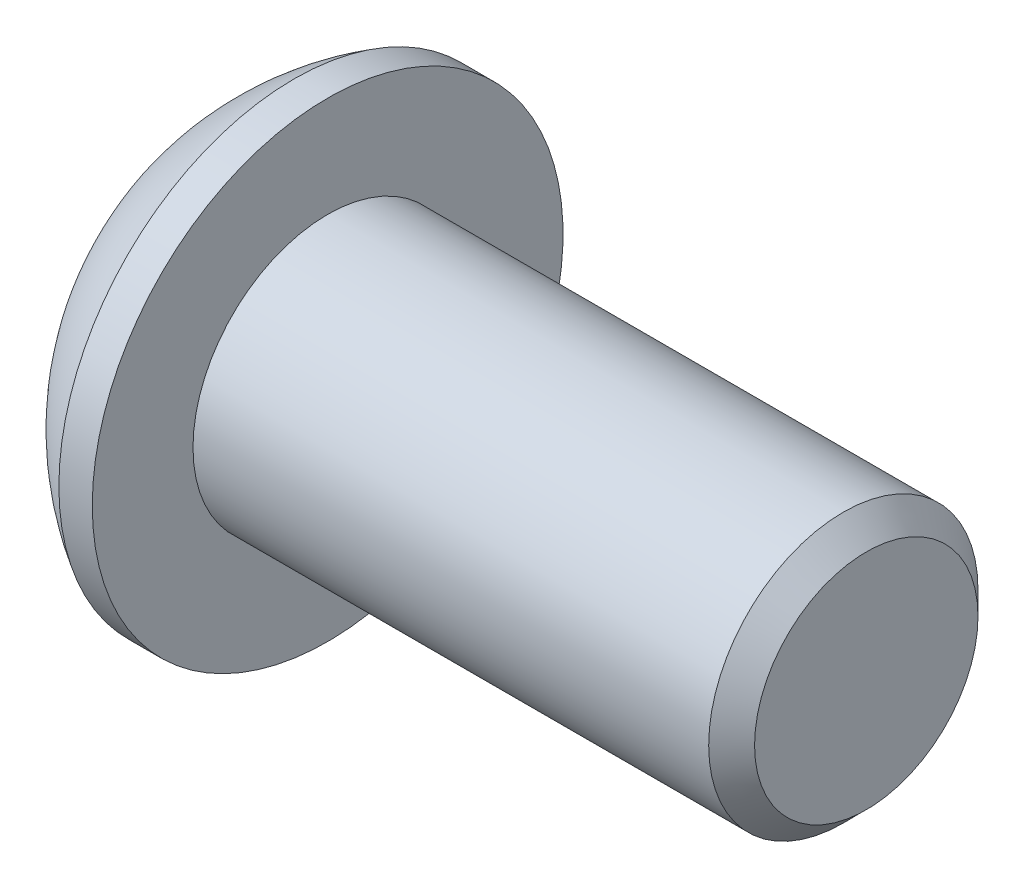
SolidWorks part; units mm, degrees
ref_plane "Plane1" through (0, 0, 0) normal (0, 0, 1) x (1, 0, 0)
ref_plane "Plane2" through (0, 0, 0) normal (0, 1, 0) x (1, 0, 0)
ref_plane "Plane3" through (0, 0, 0) normal (1, 0, 0) x (0, 0, -1)
sketch "BodySke" plane through (0, 0, 0) normal (0, 0, 1) x (1, 0, 0)
  line L0 (16.0528, 0) -> (16.0528, 2.634)
  line L1 (15.5118, 3.175) -> (3.3528, 3.175)
  line L2 (3.3528, 3.175) -> (3.3528, 5.5499)
  line L3 (3.3528, 5.5499) -> (2.5654, 5.5499)
  line L4 (0, 0) -> (101.6, 0) construction
  line L5 (3.3528, -5.5499) -> (2.5654, -5.5499) construction
  line L6 (55.6768, -3.175) -> (3.3528, -3.175) construction
  line L7 (16.0528, 0) -> (0, 0)
  line L8 (0, 2.775) -> (0, -2.775) construction
  line L9 (0, 0) -> (0, 2.775)
  line L10 (16.0528, 2.634) -> (15.5118, 3.175)
  line L11 (16.0528, -2.634) -> (15.5118, -3.175) construction
  line L12 (4.2596, 9.525) -> (4.2596, -3.175) construction
  line L13 (3.3528, 9.525) -> (3.3528, -3.175) construction
  arc A1 (0, 2.775) -> (2.5654, 5.5499) centre (5.7851, 0) cw
  dimension "Diameter" = 6.35
  dimension "Length" = 12.7
  dimension "Head_dia" = 11.0998
  dimension "D1" = 5.5499
  dimension "Head_ht" = 3.3528
  dimension "Head_side_ht" = 0.7874
  dimension "Minor_dia" = 5.268
  dimension "Body_ch_ang" = 45
  dimension "Advance" = 0.9068
  dimension "Thread_nom" = 12.7
revolve "BaseBody" add sketch "BodySke" angle 360 about L4
cosmetic thread "ThreadCosmetic" [suppressed] parameters "Thread_length"=11.7932, "Thread_minor"=5.268
sketch "Sketch2" plane through (0, 0, 0) normal (0, 0, 1) x (1, 0, 0)
  line L0 (0, 1.9812) -> (2.2098, 1.9812)
  line L1 (2.2098, 1.9812) -> (3.3536, 0)
  line L3 (3.3536, 0) -> (0, 0)
  line L4 (0, 0) -> (0, 1.9812)
  line L5 (0, -1.9812) -> (2.2098, -1.9812) construction
  line L6 (0, 0) -> (47.625, 0) construction
  dimension "D2" = 60
  dimension "PreBroach_depth" = 2.2098
  dimension "PreBroach_dia" = 3.9624
revolve "PreBroach" cut sketch "Sketch2" angle 360 about L6
sketch "Sketch3" plane through (0, 0, 0) normal (1, 0, 0) x (0, 0, -1)
  line L0 (-1.9812, -1.1438) -> (-1.9812, 1.1438)
  line L1 (-1.9812, 1.1438) -> (0, 2.2877)
  line L2 (0, 2.2877) -> (1.9812, 1.1438)
  line L3 (1.9812, 1.1438) -> (1.9812, -1.1438)
  line L4 (1.9812, -1.1438) -> (0, -2.2877)
  line L5 (0, -2.2877) -> (-1.9812, -1.1438)
  dimension "Hex_size" = 3.9624
  dimension "D3" = 3.9624
  dimension "D1" = 1.9812
  dimension "D2" = 1.9812
extrude "Hex" cut sketch "Sketch3" along normal blind 2.2098
sketch "Sketch4" plane through (0, 9.525, 0) normal (1, 0, 0) x (0, 0, -1)
  line L0 (0, -9.525) -> (2.3876, -9.525)
  line L1 (0, -9.525) -> (6.1484, -5.9752) construction
  line L2 (0, -9.525) -> (1.1938, -7.4573)
  line L3 (1.9883, -8.949) -> (2.2704, -8.7861)
  line L4 (1.493, -8.0911) -> (1.7751, -7.9282)
  arc A0 (1.9883, -8.949) -> (1.493, -8.0911) centre (0, -9.525) ccw
  arc A1 (2.3876, -9.525) -> (2.2704, -8.7861) centre (0, -9.525) ccw
  arc A2 (1.1938, -7.4573) -> (1.7751, -7.9282) centre (0, -9.525) cw
  dimension "Spline_n_dim" = 4.1402
  dimension "Spline_m_dim" = 4.7752
  dimension "D1" = 30
  dimension "D2" = 60
  dimension "Spline_p_dim" = 0.9906
  dimension "D3" = 0.4953
extrude "Spline" [suppressed] cut sketch "Sketch4" along normal blind 2.2098
pattern_circular "CirPattern1" [suppressed] count 6 every 60 about axis through (0, 0, 0) along (1, 0, 0)
sketch "ThdSchSke" plane through (0, 0, 0) normal (0, 0, 1) x (1, 0, 0)
  line L0 (4.2596, -2.634) -> (3.8808, -3.175)
  line L1 (4.2596, -2.634) -> (4.6384, -3.175)
  line L2 (4.6384, -3.175) -> (4.6384, -3.9688)
  line L3 (-3.175, 0) -> (5.1513, 0) construction
  line L5 (4.6384, -3.9688) -> (3.8808, -3.9688)
  line L6 (3.8808, -3.9688) -> (3.8808, -3.175)
  dimension "Diameter" = 6.35
  dimension "Thread_minor" = 5.268
  dimension "SideAngle" = 55
  dimension "VeeAngle" = 70
  dimension "Overcut" = 7.9375
  dimension "Start" = 4.2596
revolve "ThreadSchematic" [suppressed] cut sketch "ThdSchSke" angle 360 about L3
pattern_linear "ThdSchPat" [suppressed]
equation "\"D1@BodySke\" = \"Head_dia@BodySke\" * .5"
equation "\"Thread_minor@ThreadCosmetic\" = \"Minor_dia@BodySke\""
equation "\"D1@Sketch3\" = \"Hex_size@Sketch3\" / 2"
equation "\"D2@Sketch3\" = \"D1@Sketch3\""
equation "\"D3@Sketch3\" = \"Hex_size@Sketch3\""
equation "\"D3@Sketch4\" = \"Spline_p_dim@Sketch4\" / 2"
equation "\"D1@Sketch4\" = \"D2@Sketch4\" / 2"
equation "\"Thread_length@ThreadCosmetic\" = ((sgn( (\"Length@BodySke\" - \"Advance@BodySke\" ) - \"Thread_nom@BodySke\" )-1)*( (\"Length@BodySke\" - \"Advance@BodySke\" ) - \"Thread_nom@BodySke\" ))/-2+ \"Thread_nom@BodySke\""
equation "\"Thread_minor@ThdSchSke\" = \"Minor_dia@BodySke\""
equation "\"Diameter@ThdSchSke\" = \"Diameter@BodySke\""
equation "\"Overcut@ThdSchSke\" = \"Diameter@BodySke\" * 1.25"
equation "\"Start@ThdSchSke\" = \"Head_ht@BodySke\" + \"Length@BodySke\" - \"Thread_length@ThreadCosmetic\"  '---Non-countersunk---"
equation "\"Num_threads@ThdSchPat\" = int( \"Thread_length@ThreadCosmetic\" / \"Advance@BodySke\" + 0.999 )  + 1"
equation "\"Advance@ThdSchPat\" = \"Thread_length@ThreadCosmetic\" /  (\"Num_threads@ThdSchPat\" - 1) 'relax it"
equation "\"Num_threads@ThdSchPat\" = \"Num_threads@ThdSchPat\" - sgn( \"Num_threads@ThdSchPat\" - 1) '---chamfered tips only---"
